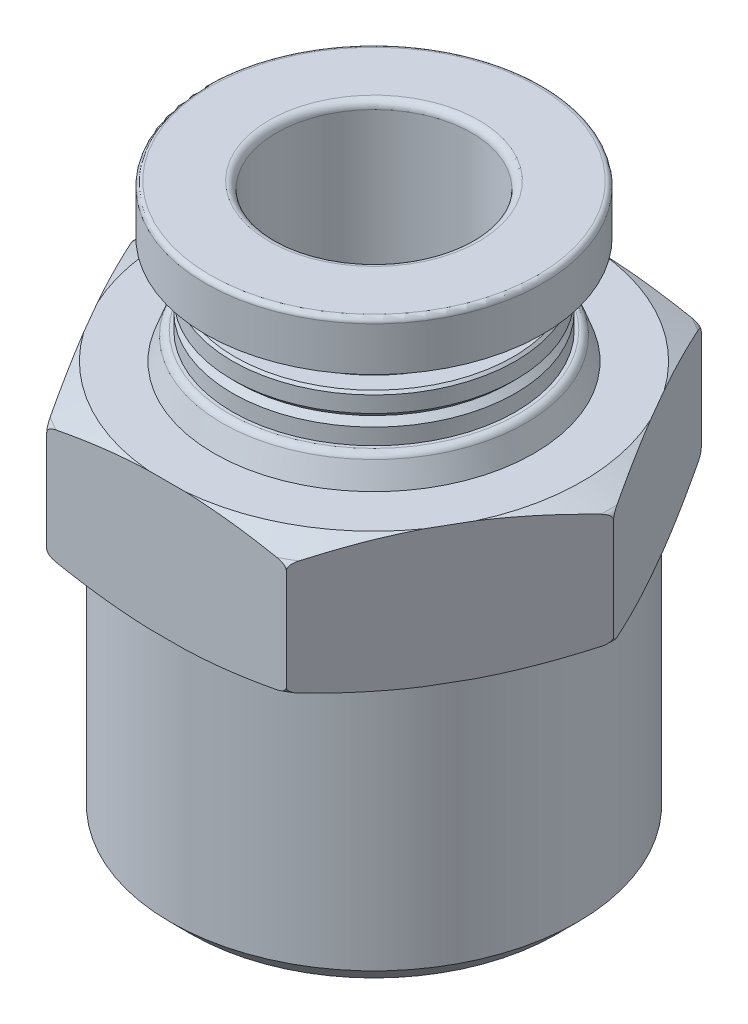
SolidWorks part; units mm, degrees
material "标准件"
ref_plane "前视基准面" through (0, 0, 0) normal (0, 0, 1) x (1, 0, 0)
ref_plane "上视基准面" through (0, 0, 0) normal (0, 1, 0) x (1, 0, 0)
ref_plane "右视基准面" through (0, 0, 0) normal (1, 0, 0) x (0, 0, -1)
ref_plane "基准面1" through (0, 11, 0) normal (0, 1, 0) x (1, 0, 0)
sketch "草图1" plane through (0, 0, 0) normal (0, 0, 1) x (1, 0, 0)
  line L0 (3, 5) -> (3, 0.6)
  line L1 (3, 0.6) -> (3.6, 0)
  line L2 (3.6, 0) -> (7.475, 0)
  line L3 (7.475, 0) -> (8.331, 0.856)
  line L4 (8.331, 0.856) -> (8.331, 11)
  line L5 (8.331, 11) -> (8.535, 11)
  line L6 (8.535, 11) -> (9.6298, 11.4535)
  line L7 (9.815, 11.7306) -> (9.815, 15.8694)
  line L8 (9.6298, 16.1465) -> (8.535, 16.6)
  line L9 (8.535, 16.6) -> (6.55, 16.6)
  line L10 (6.55, 16.6) -> (6.2156, 17.5041)
  line L11 (5.9342, 17.7) -> (5.8, 17.7)
  line L12 (5.8, 17.7) -> (5.8, 18.36)
  line L13 (5.8, 18.36) -> (5.56, 18.6)
  line L14 (5.56, 18.6) -> (5.8, 18.84)
  line L15 (5.8, 18.84) -> (5.8, 19.5)
  line L16 (5.8, 19.5) -> (5.7, 19.6)
  line L17 (5.7, 19.6) -> (4.95, 19.6)
  line L18 (4.95, 19.6) -> (4.95, 21)
  line L19 (4.95, 21) -> (6.9, 21)
  line L20 (6.9, 21) -> (6.9, 22.8)
  line L21 (6.7, 23) -> (4.3, 23)
  line L22 (4, 22.7) -> (4, 5)
  line L23 (4, 5) -> (3, 5)
  line L24 (0, 0) -> (0, 23) construction
  arc A0 (9.6298, 11.4535) -> (9.815, 11.7306) centre (9.515, 11.7306) ccw
  arc A1 (9.815, 15.8694) -> (9.6298, 16.1465) centre (9.515, 15.8694) ccw
  arc A2 (6.2156, 17.5041) -> (5.9342, 17.7) centre (5.9342, 17.4) ccw
  arc A3 (6.9, 22.8) -> (6.7, 23) centre (6.7, 22.8) ccw
  arc A4 (4.3, 23) -> (4, 22.7) centre (4.3, 22.7) ccw
revolve "旋转1" add sketch "草图1" angle 360 about L24
cosmetic thread "装饰螺纹线1" parameters "D1"=11, "D2"=14.95
sketch "草图2" plane through (0, 11, 0) normal (0, 1, 0) x (1, 0, 0)
  line L0 (-9.815, 0) -> (-4.9075, -8.5)
  line L1 (-4.9075, -8.5) -> (4.9075, -8.5)
  line L2 (4.9075, -8.5) -> (9.815, 0)
  line L3 (9.815, 0) -> (4.9075, 8.5)
  line L4 (4.9075, 8.5) -> (-4.9075, 8.5)
  line L5 (-4.9075, 8.5) -> (-9.815, 0)
  circle A0 centre (0, 0) radius 11.815
extrude "切除-拉伸1" cut sketch "草图2" along normal blind 23
